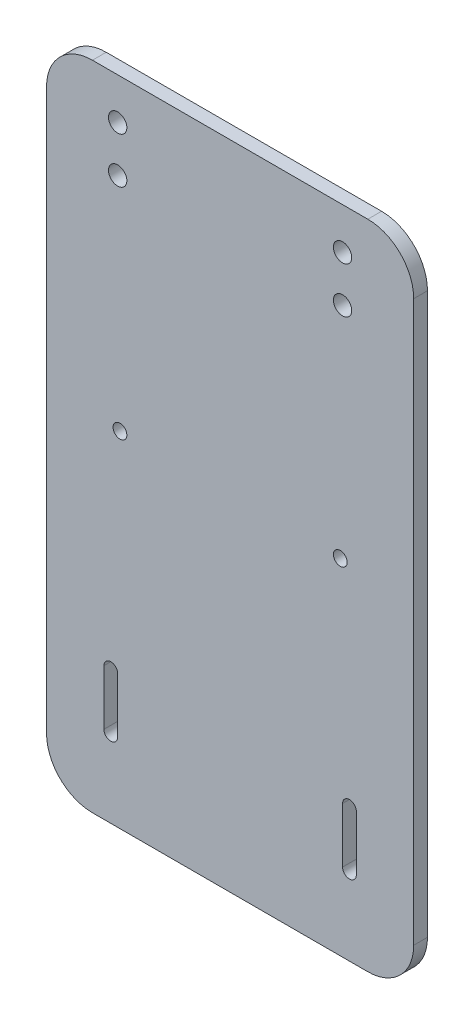
SolidWorks part; units mm, degrees
material "6061 合金"
ref_plane "前视基准面" through (0, 0, 0) normal (0, 0, 1) x (1, 0, 0)
ref_plane "上视基准面" through (0, 0, 0) normal (0, 1, 0) x (1, 0, 0)
ref_plane "右视基准面" through (0, 0, 0) normal (1, 0, 0) x (0, 0, -1)
sketch "草图1" plane through (0, 0, 0) normal (0, 0, 1) x (1, 0, 0)
  line L0 (0, 0) -> (0, 75) construction
  line L1 (-40, 75) -> (40, 75)
  line L2 (-40, 75) -> (-40, -75)
  line L3 (-40, -75) -> (40, -75)
  line L4 (40, 75) -> (40, -75)
  line L5 (-40, 75) -> (40, -75) construction
  line L6 (-40, -75) -> (40, 75) construction
  line L7 (24, 0) -> (-24, 0) construction
  circle A0 centre (24, 0) radius 1.5
  circle A1 centre (-24, 0) radius 1.5
  circle A2 centre (24.5, 48) radius 1.5
  circle A3 centre (-24.5, 48) radius 1.5
  circle A4 centre (26, -58) radius 1.5
  circle A5 centre (-26, -58) radius 1.5
  point P0 (0, 0)
  dimension "D3" = 48
  dimension "D4" = 3
  dimension "D5" = 3
  dimension "D6" = 49
  dimension "D7" = 48
  dimension "D8" = 3
  dimension "D9" = 52
  dimension "D1" = 150
  dimension "D2" = 80
  dimension "D10" = 58
extrude "凸台-拉伸1" add sketch "草图1" along normal blind 3
sketch "草图2" plane through (0, 0, 3) normal (0, 0, 1) x (1, 0, 0)
  line L0 (-26, -58) -> (-26, -46) construction
  line L1 (-27.5, -58) -> (-27.5, -46)
  line L2 (-24.5, -58) -> (-24.5, -46)
  line L3 (0, 75) -> (0, -75) construction
  line L4 (40, 75) -> (-40, 75) construction
  line L5 (-40, -75) -> (40, -75) construction
  line L6 (26, -58) -> (26, -46) construction
  line L7 (27.5, -58) -> (27.5, -46)
  line L8 (24.5, -58) -> (24.5, -46)
  arc A0 (-27.5, -58) -> (-24.5, -58) centre (-26, -58) ccw
  arc A1 (-24.5, -46) -> (-27.5, -46) centre (-26, -46) ccw
  arc A2 (27.5, -58) -> (24.5, -58) centre (26, -58) cw
  arc A3 (24.5, -46) -> (27.5, -46) centre (26, -46) cw
  point P3 (-26, -52)
  point P16 (26, -52)
  dimension "D1" = 1.5
  dimension "D2" = 12
extrude "切除-拉伸1" cut sketch "草图2" against normal blind 10
sketch "草图3" plane through (0, 0, 3) normal (0, 0, 1) x (1, 0, 0)
  line L0 (24.5, 48) -> (24.5, 58) construction
  line L1 (0, 75) -> (0, 42.9327) construction
  line L2 (40, 75) -> (-40, 75) construction
  circle A0 centre (24.5, 58) radius 2
  circle A1 centre (24.5, 48) radius 2
  circle A2 centre (-24.5, 48) radius 2
  circle A3 centre (-24.5, 58) radius 2
  dimension "D2" = 4
  dimension "D3" = 4
  dimension "D1" = 10
extrude "切除-拉伸2" cut sketch "草图3" against normal blind 10
sketch "草图4" plane through (0, 0, 3) normal (0, 0, 1) x (1, 0, 0)
  line L1 (-40, 75) -> (47.19, 75)
  line L2 (-40, 75) -> (-40, 67)
  line L3 (-40, 67) -> (47.19, 67)
  line L4 (47.19, 75) -> (47.19, 67)
  dimension "D1" = 8
  dimension "D2" = 87.19
extrude "切除-拉伸3" cut sketch "草图4" against normal blind 10
fillet "圆角1" radius 10 4 edges at (-40, 67, 1.5) (40, 67, 1.5) (40, -75, 1.5) (-40, -75, 1.5)
